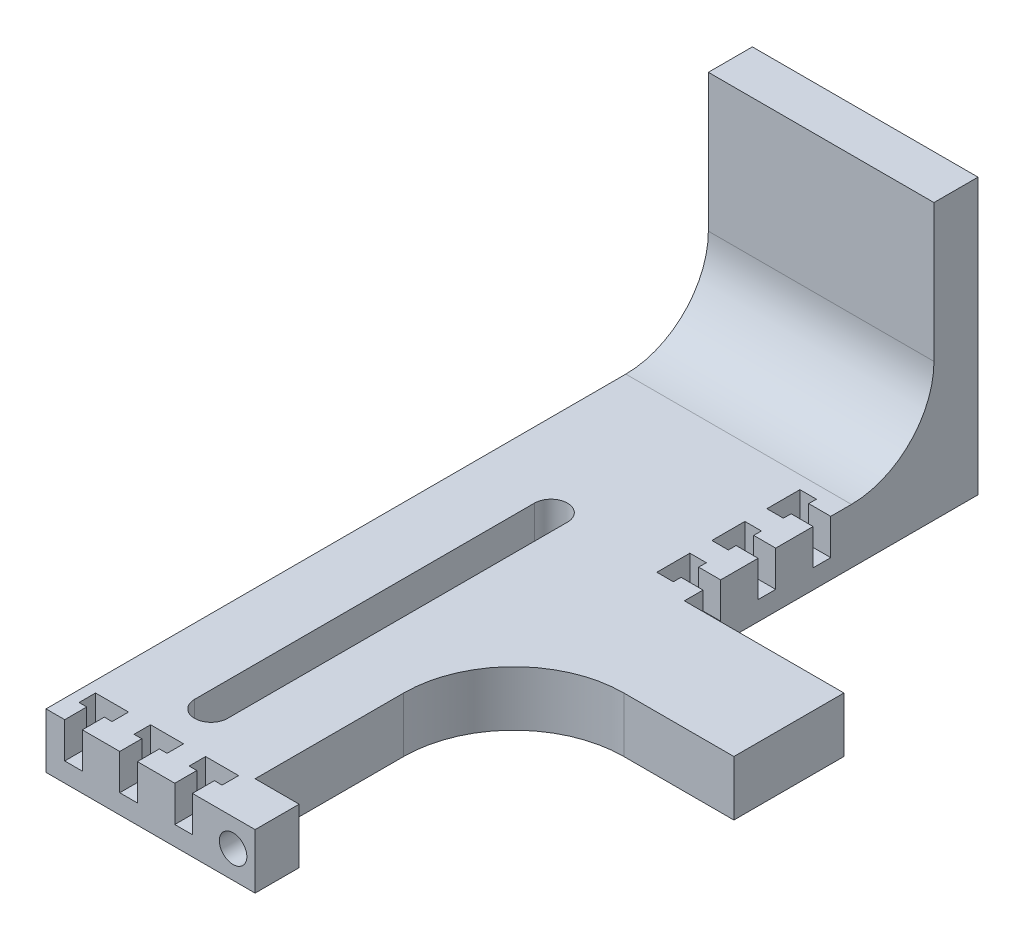
SolidWorks part; units mm, degrees
ref_plane "前视基准面" through (0, 0, 0) normal (0, 0, 1) x (1, 0, 0)
ref_plane "上视基准面" through (0, 0, 0) normal (0, 1, 0) x (1, 0, 0)
ref_plane "右视基准面" through (0, 0, 0) normal (1, 0, 0) x (0, 0, -1)
other "Configuration Table"
sketch "草图1" plane through (0, 0, 0) normal (0, 1, 0) x (1, 0, 0)
  line L0 (0, 105) -> (0, 75)
  line L1 (0, 0) -> (30, 0)
  line L2 (0, 0) -> (0, 75)
  line L3 (0, 105) -> (30, 105)
  line L4 (30, 0) -> (30, 75)
  line L13 (30, 105) -> (41, 105)
  line L15 (30, 75) -> (41, 75)
  line L16 (41, 105) -> (41, 75)
  dimension "D1" = 30
  dimension "D2" = 105
  dimension "D3" = 11
  dimension "D4" = 30
extrude "凸台-拉伸1" add sketch "草图1" along normal blind 10
sketch "草图4" plane through (0, 10, 0) normal (0, 1, 0) x (1, 0, 0)
  line L0 (15, 15) -> (15, 76.7616) construction
  line L1 (12, 15) -> (12, 76.7616)
  line L2 (18, 15) -> (18, 76.7616)
  line L3 (15, 0) -> (15, -50000) construction
  line L4 (0, 0) -> (30, 0) construction
  arc A0 (12, 15) -> (18, 15) centre (15, 15) ccw
  arc A1 (18, 76.7616) -> (12, 76.7616) centre (15, 76.7616) ccw
  point P2 (15, 45.8808)
  point P11 (15, 0)
  dimension "D2" = 15
  dimension "D1" = 6
extrude "切除-拉伸3" cut sketch "草图4" against normal blind 16
sketch "草图6" plane through (0, 10, 0) normal (0, 1, 0) x (1, 0, 0)
  line L0 (41, 75) -> (41, 105) construction
  line L1 (41, 101.6) -> (37, 101.6)
  line L2 (41, 101.6) -> (41, 98.4)
  line L3 (41, 98.4) -> (37, 98.4)
  line L4 (37, 101.6) -> (37, 98.4)
  line L5 (0, 0) -> (30, 0) construction
  line L6 (3.4, 0) -> (6.6, 0)
  line L7 (3.4, 0) -> (3.4, 4)
  line L8 (3.4, 4) -> (6.6, 4)
  line L9 (6.6, 0) -> (6.6, 4)
  line L10 (0, 105) -> (0, 0) construction
  line L11 (41, 105) -> (0, 105) construction
  line L12 (37, 91.6) -> (37, 88.4)
  line L13 (41, 91.6) -> (37, 91.6)
  line L14 (41, 88.4) -> (37, 88.4)
  line L15 (41, 91.6) -> (41, 88.4)
  line L16 (37, 81.6) -> (37, 78.4)
  line L17 (41, 81.6) -> (37, 81.6)
  line L18 (41, 78.4) -> (37, 78.4)
  line L19 (41, 81.6) -> (41, 78.4)
  line L20 (13.4, 0) -> (16.6, 0)
  line L21 (16.6, 0) -> (16.6, 4)
  line L22 (13.4, 4) -> (16.6, 4)
  line L23 (13.4, 0) -> (13.4, 4)
  line L24 (23.4, 0) -> (26.6, 0)
  line L25 (26.6, 0) -> (26.6, 4)
  line L26 (23.4, 4) -> (26.6, 4)
  line L27 (23.4, 0) -> (23.4, 4)
  dimension "D1" = 4
  dimension "D2" = 3.2
  dimension "D3" = 3.4
  dimension "D4" = 3.4
  dimension "D5" = 3.2
  dimension "D6" = 4
  dimension "D7" = 3
extrude "切除-拉伸5" cut sketch "草图6" against normal blind 6.5
sketch "草图7" plane through (0, 10, 0) normal (0, 1, 0) x (1, 0, 0)
  line L1 (2, 4) -> (8, 4)
  line L2 (2, 4) -> (2, 7)
  line L3 (2, 7) -> (8, 7)
  line L4 (8, 4) -> (8, 7)
  line L5 (0, 105) -> (0, 0) construction
  line L6 (12, 4) -> (18, 4)
  line L7 (18, 4) -> (18, 7)
  line L8 (12, 7) -> (18, 7)
  line L9 (12, 4) -> (12, 7)
  line L10 (22, 4) -> (28, 4)
  line L11 (28, 4) -> (28, 7)
  line L12 (22, 7) -> (28, 7)
  line L13 (22, 4) -> (22, 7)
  line L14 (41, 105) -> (0, 105) construction
  line L15 (37, 97) -> (34, 97)
  line L16 (37, 97) -> (37, 103)
  line L17 (37, 103) -> (34, 103)
  line L18 (34, 97) -> (34, 103)
  line L19 (34, 87) -> (34, 93)
  line L20 (37, 93) -> (34, 93)
  line L21 (37, 87) -> (37, 93)
  line L22 (37, 87) -> (34, 87)
  line L23 (34, 77) -> (34, 83)
  line L24 (37, 83) -> (34, 83)
  line L25 (37, 77) -> (37, 83)
  line L26 (37, 77) -> (34, 77)
  line L27 (0, 0) -> (3.4, 0) construction
  line L28 (41, 101.6) -> (41, 105) construction
  dimension "D1" = 3
  dimension "D2" = 6
  dimension "D3" = 2
  dimension "D4" = 3
  dimension "D5" = 6
  dimension "D6" = 2
  dimension "D9" = 4
  dimension "D10" = 4
  dimension "D8" = 3
  dimension "D7" = 3
extrude "切除-拉伸6" cut sketch "草图7" against normal blind 16.5
sketch "草图8" plane through (0, 0, 0) normal (0, -1, 0) x (1, 0, 0)
  line L1 (30, -75) -> (70, -75)
  line L2 (30, -75) -> (30, -55)
  line L3 (30, -55) -> (70, -55)
  line L4 (70, -75) -> (70, -55)
  dimension "D1" = 40
  dimension "D2" = 20
extrude "凸台-拉伸2" add sketch "草图8" against normal blind 10
sketch "草图9" plane through (0, 0, -105) normal (0, 0, -1) x (-1, 0, 0)
  line L1 (-41, 0) -> (0, 0)
  line L2 (-41, 0) -> (-41, 10)
  line L3 (-41, 10) -> (0, 10)
  line L4 (0, 0) -> (0, 10)
extrude "凸台-拉伸3" add sketch "草图9" along normal blind 23.36
sketch "草图10" plane through (0, 10, 0) normal (0, 1, 0) x (1, 0, 0)
  line L0 (41, 101.6) -> (41, 128.36) construction
  line L1 (0, 128.36) -> (41, 128.36)
  line L2 (0, 128.36) -> (0, 120.36)
  line L3 (0, 120.36) -> (41, 120.36)
  line L4 (41, 128.36) -> (41, 120.36)
  dimension "D1" = 8
extrude "凸台-拉伸4" add sketch "草图10" along normal blind 40
sketch "草图11" plane through (0, 0, 0) normal (0, -1, 0) x (1, 0, 0)
  line L1 (30, 0) -> (38, 0)
  line L2 (30, 0) -> (30, -8)
  line L3 (30, -8) -> (38, -8)
  line L4 (38, 0) -> (38, -8)
  dimension "D1" = 8
  dimension "D2" = 8
extrude "凸台-拉伸5" add sketch "草图11" against normal blind 10
sketch "草图12" plane through (0, 0, -8) normal (0, 0, -1) x (-1, 0, 0)
  line L0 (-30, 10) -> (-30, 0) construction
  line L1 (-30, 0) -> (-38, 0) construction
  circle A0 centre (-34, 5) radius 2.5
  dimension "D2" = 5
  dimension "D3" = 5
  dimension "D1" = 4
extrude "切除-拉伸7" cut sketch "草图12" against normal blind 10
fillet "圆角1" radius 20 1 edges at (30, 5, -55)
fillet "圆角2" radius 15 1 edges at (20.5, 10, -120.36)
